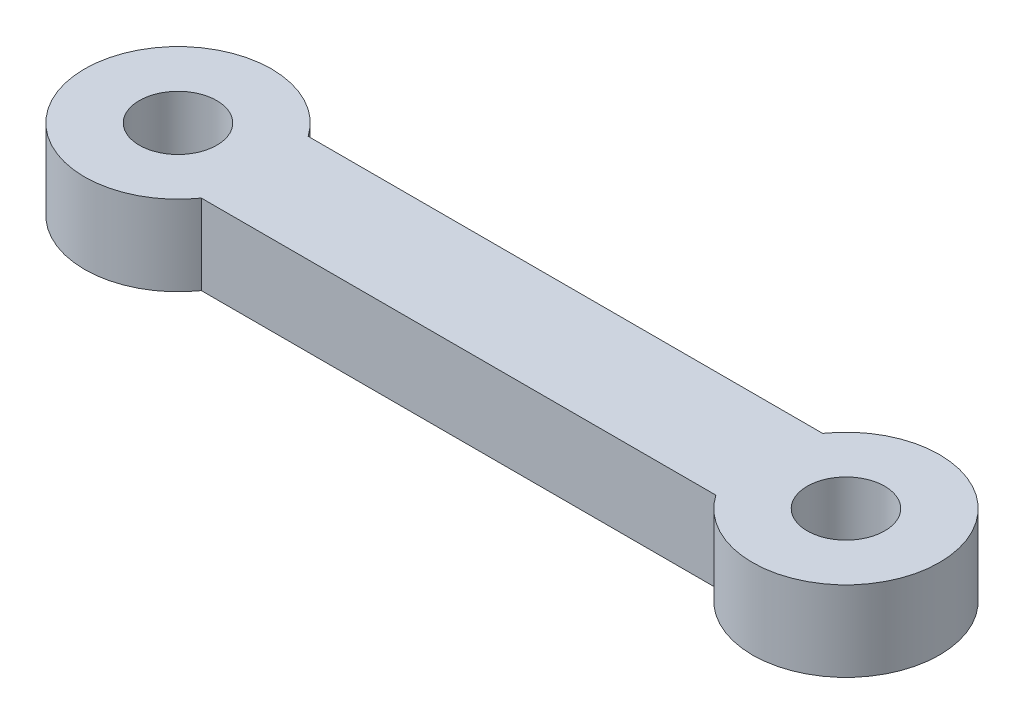
SolidWorks part; units mm, degrees
ref_plane "Front Plane" through (0, 0, 0) normal (0, 0, 1) x (1, 0, 0)
ref_plane "Top Plane" through (0, 0, 0) normal (0, 1, 0) x (1, 0, 0)
ref_plane "Right Plane" through (0, 0, 0) normal (1, 0, 0) x (0, 0, -1)
sketch "Sketch1" plane through (0, 0, 0) normal (0, 1, 0) x (1, 0, 0)
  line L0 (0, 0) -> (1.8415, 0) construction
  line L1 (3.6478, 2.54) -> (28.1022, 2.54)
  line L2 (3.6478, -2.54) -> (28.1022, -2.54)
  line L3 (0, 0) -> (31.75, 0) construction
  line L5 (29.9085, 0) -> (31.75, 0) construction
  arc A0 (3.6478, 2.54) -> (3.6478, -2.54) centre (0, 0) ccw
  arc A1 (28.1022, -2.54) -> (28.1022, 2.54) centre (31.75, 0) ccw
  circle A2 centre (0, 0) radius 1.8415
  circle A3 centre (31.75, 0) radius 1.8415
  dimension "D1" = 8.89
  dimension "D3" = 8.89
  dimension "D5" = 3.683
  dimension "D6" = 3.683
  dimension "D2" = 31.75
  dimension "D4" = 2.54
  dimension "D7" = 2.54
extrude "Boss-Extrude1" add sketch "Sketch1" along normal blind 3.81
